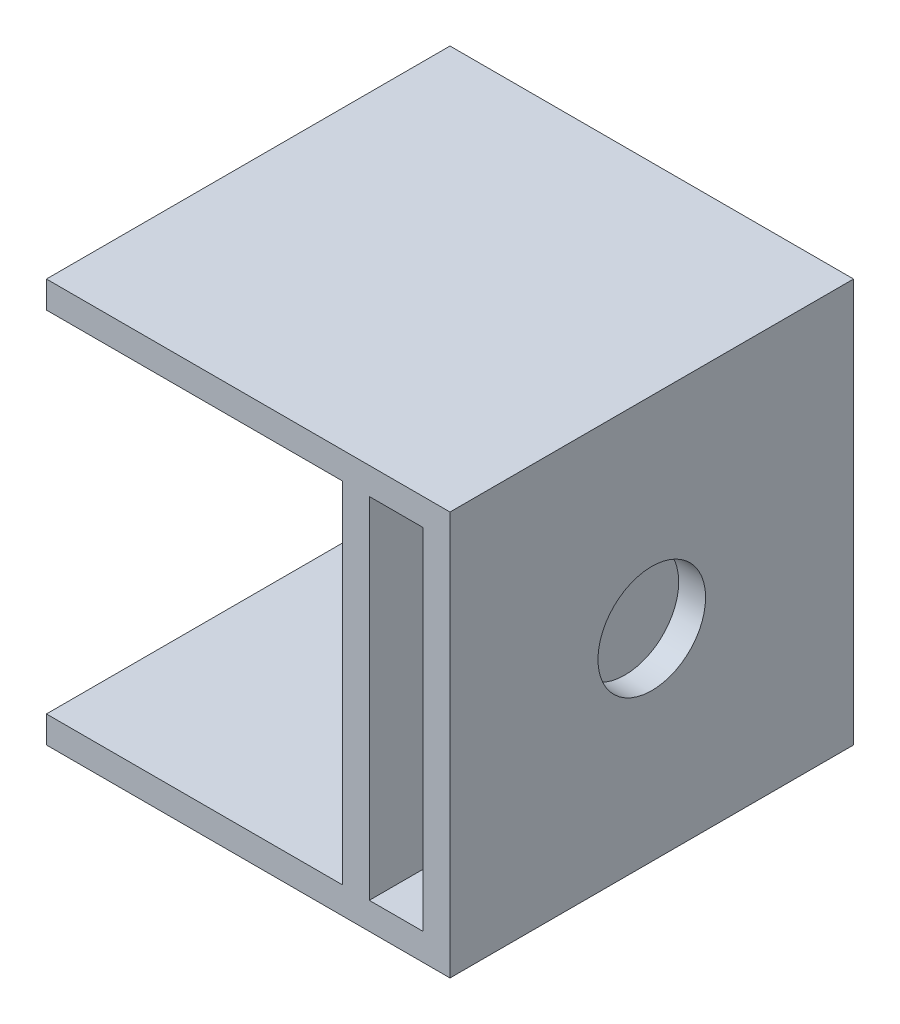
SolidWorks part; units mm, degrees
ref_plane "Front Plane" through (0, 0, 0) normal (0, 0, 1) x (1, 0, 0)
ref_plane "Top Plane" through (0, 0, 0) normal (0, 1, 0) x (1, 0, 0)
ref_plane "Right Plane" through (0, 0, 0) normal (1, 0, 0) x (0, 0, -1)
sketch "Sketch1" plane through (0, 0, 0) normal (0, 0, 1) x (1, 0, 0)
  line L0 (-17.8613, 18.2225) -> (12.1387, 18.2225)
  line L1 (12.1387, 18.2225) -> (12.1387, -11.7775)
  line L2 (12.1387, -11.7775) -> (-17.8613, -11.7775)
  line L3 (-17.8613, 18.2225) -> (-17.8613, 16.2225)
  line L4 (-17.8613, 16.2225) -> (4.1387, 16.2225)
  line L5 (10.1387, 16.2225) -> (10.1387, -9.7775)
  line L6 (10.1387, -9.7775) -> (6.1387, -9.7775)
  line L7 (-17.8613, -9.7775) -> (-17.8613, -11.7775)
  line L8 (4.1387, 16.2225) -> (4.1387, -9.7775)
  line L9 (6.1387, 16.2225) -> (6.1387, -9.7775)
  line L10 (6.1387, 16.2225) -> (10.1387, 16.2225)
  line L11 (4.1387, -9.7775) -> (-17.8613, -9.7775)
  dimension "D1" = 30
  dimension "D2" = 30
  dimension "D3" = 30
  dimension "D4" = 2
  dimension "D5" = 2
  dimension "D6" = 2
  dimension "D7" = 2
  dimension "D8" = 22
extrude "Boss-Extrude1" add sketch "Sketch1" along normal blind 30
sketch "Sketch2" plane through (12.1387, 0, 0) normal (1, 0, 0) x (0, 0, -1)
  line L0 (-30, 18.2225) -> (0, 18.2225) construction
  circle A0 centre (-15, 3.2225) radius 4
  point P4 (-15, 18.2225)
  dimension "D1" = 8
extrude "Cut-Extrude1" cut sketch "Sketch2" against normal blind 30
